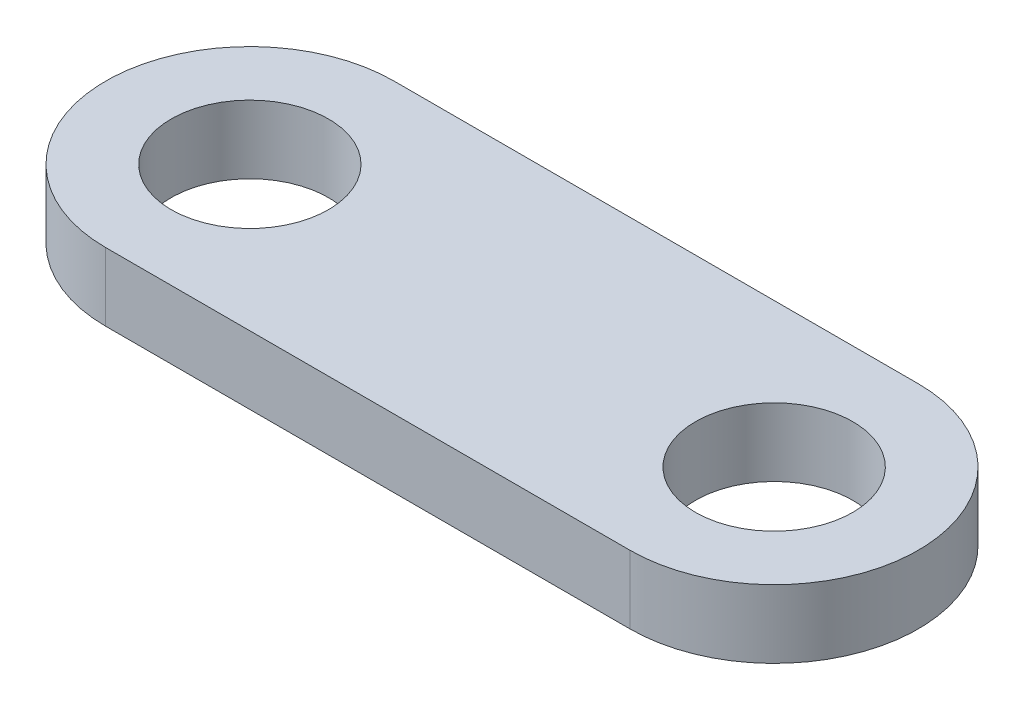
SolidWorks part; units mm, degrees
ref_plane "前视基准面" through (0, 0, 0) normal (0, 0, 1) x (1, 0, 0)
ref_plane "上视基准面" through (0, 0, 0) normal (0, 1, 0) x (1, 0, 0)
ref_plane "右视基准面" through (0, 0, 0) normal (1, 0, 0) x (0, 0, -1)
other "Configuration Table"
sketch "草图1" plane through (0, 0, 0) normal (0, 1, 0) x (1, 0, 0)
  line L0 (-10, 0) -> (10, 0) construction
  line L1 (-10, 5.5) -> (10, 5.5)
  line L2 (-10, -5.5) -> (10, -5.5)
  arc A0 (-10, 5.5) -> (-10, -5.5) centre (-10, 0) ccw
  arc A1 (10, -5.5) -> (10, 5.5) centre (10, 0) ccw
  circle A2 centre (-10, 0) radius 3
  circle A3 centre (10, 0) radius 3
  point P2 (0, 0)
  dimension "D2" = 5.5
  dimension "D3" = 6
  dimension "D4" = 6
  dimension "D1" = 20
extrude "凸台-拉伸1" add sketch "草图1" along normal blind 2.6
